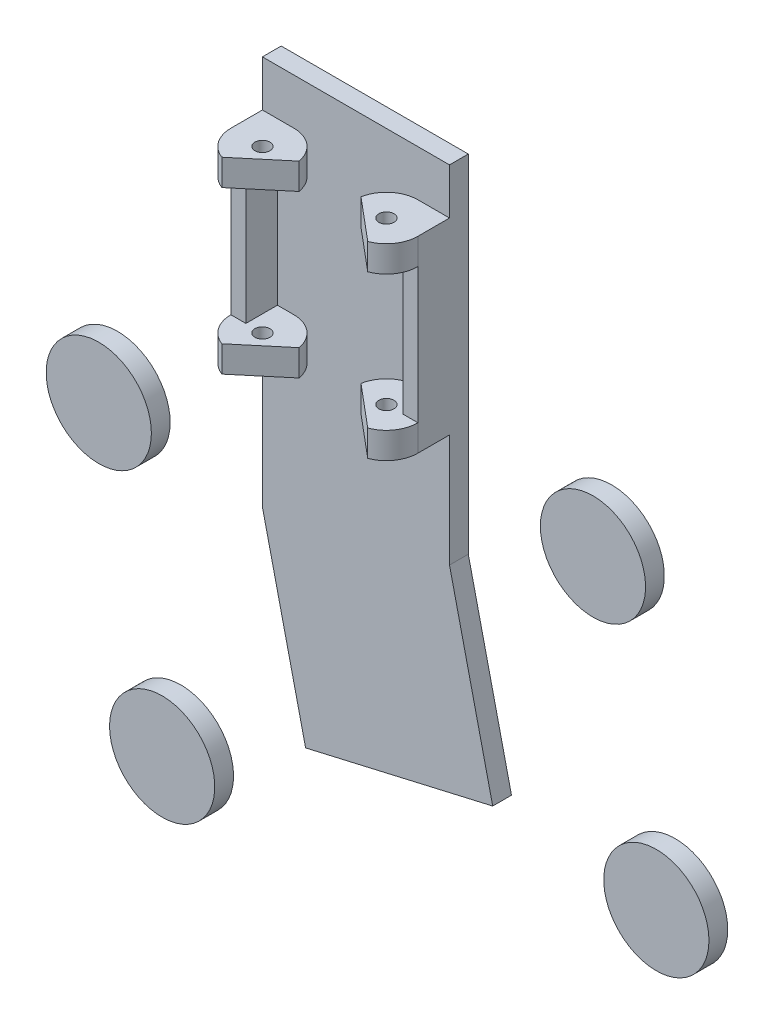
SolidWorks part; units mm, degrees
ref_plane "Front Plane" through (0, 0, 0) normal (0, 0, 1) x (1, 0, 0)
ref_plane "Top Plane" through (0, 0, 0) normal (0, 1, 0) x (1, 0, 0)
ref_plane "Right Plane" through (0, 0, 0) normal (1, 0, 0) x (0, 0, -1)
sketch "Sketch1" plane through (0, 0, 0) normal (0, 1, 0) x (1, 0, 0)
  line L0 (0, 22.8391) -> (0, -19.8342) construction
  line L1 (-35.1495, 0) -> (37.3645, 0) construction
  line L2 (-24.9, 0) -> (-24.9, 13.4)
  line L3 (-24.9, 13.4) -> (24.9, 13.4)
  line L4 (24.9, 0) -> (24.9, 13.4)
  line L5 (-19.4124, -7.879) -> (-8.235, 1.5)
  line L6 (19.4124, -7.879) -> (8.235, 1.5)
  line L7 (16.5, 8.4) -> (-16.5, 8.4)
  arc A0 (19.4124, -7.879) -> (24.9, 0) centre (16.5, 0) ccw
  arc A1 (-19.4124, -7.879) -> (-24.9, 0) centre (-16.5, 0) cw
  arc A2 (-16.5, 8.4) -> (-8.235, 1.5) centre (-16.5, 0) cw
  arc A3 (16.5, 8.4) -> (8.235, 1.5) centre (16.5, 0) ccw
  circle A4 centre (-16.5, 0) radius 8.4 construction
  circle A5 centre (16.5, 0) radius 8.4 construction
  point P14 (0, 13.4)
  dimension "D1" = 16.8
  dimension "D2" = 33
  dimension "D3" = 5
  dimension "D4" = 130
  dimension "D5" = 1.5
  dimension "D6" = 13.4
extrude "Boss-Extrude2" add sketch "Sketch1" along normal blind 7
sketch "Sketch3" plane through (0, 7, 0) normal (0, 1, 0) x (1, 0, 0)
  circle A0 centre (-16.5, 0) radius 2
  circle A1 centre (16.5, 0) radius 2
  dimension "D1" = 4
extrude "Cut-Extrude2" cut sketch "Sketch3" against normal through all both and the other way through all
sketch "Sketch4" plane through (0, 7, 0) normal (0, 1, 0) x (1, 0, 0)
  line L0 (-24.9, 13.4) -> (-24.9, 0)
  line L1 (-24.9, 13.4) -> (24.9, 13.4)
  line L2 (24.9, 13.4) -> (24.9, 0)
  line L3 (0, 13.4) -> (0, 0) construction
  line L4 (-16.5, 8.4) -> (16.5, 8.4)
  line L5 (-16.5, 8.4) -> (16.5, 8.4) construction
  line L6 (16.5, 8.4) -> (20.9, 8.4)
  line L7 (20.9, 8.4) -> (20.9, 0)
  line L8 (20.9, 0) -> (24.9, 0)
  line L9 (-20.9, 0) -> (-24.9, 0)
  line L10 (-20.9, 8.4) -> (-20.9, 0)
  line L11 (-16.5, 8.4) -> (-20.9, 8.4)
  circle A0 centre (-16.5, 0) radius 3.7 construction
  point P21 (0, 8.4)
  dimension "D2" = 7.4
  dimension "D1" = 4
extrude "Boss-Extrude3" add sketch "Sketch4" along normal blind 36
sketch "Sketch5" plane through (0, 43, 0) normal (0, 1, 0) x (1, 0, 0)
  line L12 (-24.9, 13.4) -> (-24.9, 0)
  line L13 (24.9, 13.4) -> (-24.9, 13.4)
  line L14 (24.9, 0) -> (24.9, 13.4)
  line L15 (8.235, 1.5) -> (19.4124, -7.879)
  line L16 (-16.5, 8.4) -> (16.5, 8.4)
  line L17 (-19.4124, -7.879) -> (-8.235, 1.5)
  line L18 (-24.9, 13.4) -> (-24.9, 0)
  line L19 (24.9, 13.4) -> (-24.9, 13.4)
  line L20 (24.9, 0) -> (24.9, 13.4)
  line L21 (8.235, 1.5) -> (19.4124, -7.879)
  line L22 (-16.5, 8.4) -> (16.5, 8.4)
  line L23 (-19.4124, -7.879) -> (-8.235, 1.5)
  circle A0 centre (-16.5, 0) radius 2 construction
  circle A1 centre (16.5, 0) radius 2
  circle A2 centre (16.5, 0) radius 2 construction
  circle A4 centre (-16.5, 0) radius 2
  arc A8 (-24.9, 0) -> (-19.4124, -7.879) centre (-16.5, 0) ccw
  arc A9 (19.4124, -7.879) -> (24.9, 0) centre (16.5, 0) ccw
  arc A10 (16.5, 8.4) -> (8.235, 1.5) centre (16.5, 0) ccw
  arc A11 (-8.235, 1.5) -> (-16.5, 8.4) centre (-16.5, 0) ccw
  arc A12 (-24.9, 0) -> (-19.4124, -7.879) centre (-16.5, 0) ccw
  arc A13 (19.4124, -7.879) -> (24.9, 0) centre (16.5, 0) ccw
  arc A14 (16.5, 8.4) -> (8.235, 1.5) centre (16.5, 0) ccw
  arc A15 (-8.235, 1.5) -> (-16.5, 8.4) centre (-16.5, 0) ccw
  dimension "D1" = 0
extrude "Boss-Extrude4" add sketch "Sketch5" along normal blind 7
sketch "Sketch13" plane through (0, 50, 0) normal (0, 1, 0) x (1, 0, 0)
  line L0 (24.9, 0) -> (24.9, 13.4) construction
  line L5 (-24.9, 13.4) -> (24.9, 13.4)
  line L6 (-24.9, 13.4) -> (-24.9, 8.4)
  line L7 (-24.9, 8.4) -> (24.9, 8.4)
  line L8 (24.9, 13.4) -> (24.9, 8.4)
  line L9 (-16.5, 8.4) -> (16.5, 8.4) construction
extrude "Boss-Extrude6" add sketch "Sketch13" along normal blind 12.25
sketch "Sketch15" plane through (0, 0, 0) normal (0, -1, 0) x (1, 0, 0)
  line L0 (24.9, 0) -> (24.9, -13.4) construction
  line L1 (-24.9, -13.4) -> (24.9, -13.4)
  line L2 (-24.9, -13.4) -> (-24.9, -8.4)
  line L3 (-24.9, -8.4) -> (24.9, -8.4)
  line L4 (24.9, -13.4) -> (24.9, -8.4)
  line L5 (-16.5, -8.4) -> (16.5, -8.4) construction
extrude "Boss-Extrude7" add sketch "Sketch15" along normal blind 30
sketch "Sketch12" plane through (0, 0, -13.4) normal (0, 0, -1) x (-1, 0, 0)
  line L8 (-24.9, -30) -> (24.9, -30) construction
  line L9 (24.9, -30) -> (24.9, -41.4972) construction
  line L10 (24.9, -41.4972) -> (-24.9, -30) construction
  line L12 (0, -35.7486) -> (-11.4972, -85.5486) construction
  line L14 (-24.9, -30) -> (-36.3972, -79.8)
  line L17 (-36.3972, -79.8) -> (13.4028, -91.2972)
  line L18 (13.4028, -91.2972) -> (24.9, -41.4972)
  line L20 (24.9, -41.4972) -> (24.9, -30)
  line L21 (24.9, -30) -> (-24.9, -30)
  line L23 (-30.6486, -54.9) -> (19.1514, -66.3972) construction
  line L25 (68.457, -39.2939) -> (-63.0829, -8.9255) construction
  line L26 (68.457, -39.2939) -> (51.5857, -112.3717) construction
  line L27 (51.5857, -112.3717) -> (-79.9543, -82.0033) construction
  line L28 (-63.0829, -8.9255) -> (-79.9543, -82.0033) construction
  line L29 (68.457, -39.2939) -> (-79.9543, -82.0033) construction
  line L30 (51.5857, -112.3717) -> (-63.0829, -8.9255) construction
  circle A0 centre (-63.0829, -8.9255) radius 14
  circle A1 centre (-79.9543, -82.0033) radius 14
  circle A2 centre (68.457, -39.2939) radius 14
  circle A3 centre (51.5857, -112.3717) radius 14
  point P9 (-5.7486, -60.6486)
  dimension "D4" = 28
  dimension "D1" = 13
  dimension "D2" = 75
  dimension "D3" = 135
extrude "Boss-Extrude8" add sketch "Sketch12" against normal blind 5
